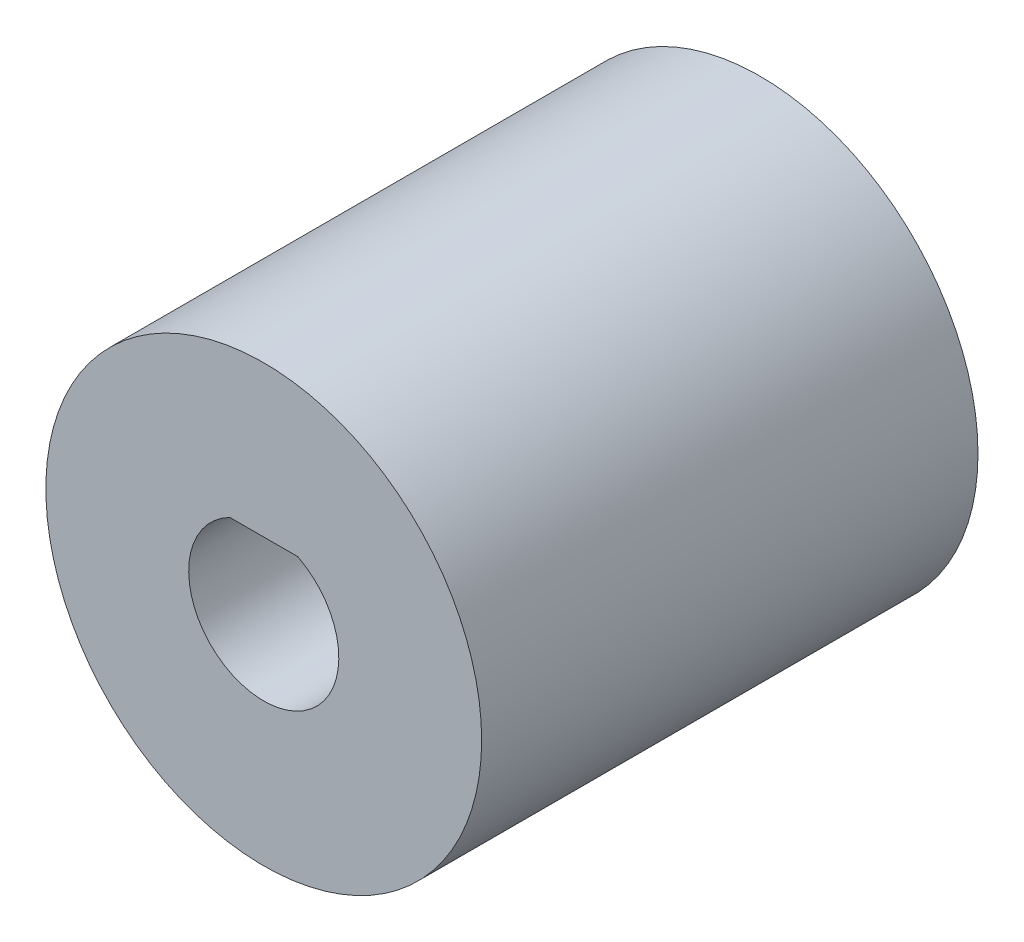
SolidWorks part; units mm, degrees
material "ABS"
ref_plane "Front Plane" through (0, 0, 0) normal (0, 0, 1) x (1, 0, 0)
ref_plane "Top Plane" through (0, 0, 0) normal (0, 1, 0) x (1, 0, 0)
ref_plane "Right Plane" through (0, 0, 0) normal (1, 0, 0) x (0, 0, -1)
sketch "Sketch2" plane through (0, 0, 0) normal (0, 0, 1) x (1, 0, 0)
  circle A0 centre (0, 0) radius 9
  circle A1 centre (0, 0) radius 6
  dimension "D1" = 18
  dimension "D2" = 12
extrude "Large Shaft Cut" add sketch "Sketch2" along normal blind 0.5
ref_plane "Plane1" through (0, 0, 0.5) normal (0, 0, 1) x (1, 0, 0)
sketch "Sketch3" plane through (0, 0, 0.5) normal (0, 0, 1) x (1, 0, 0)
  line L0 (-1.4, 2.7659) -> (1.4, 2.7659)
  circle A0 centre (0, 0) radius 9
  arc A1 (-1.4, 2.7659) -> (1.4, 2.7659) centre (0, 0) ccw
  dimension "D1" = 2.8
  dimension "D2" = 6.2
extrude "Keyed Shaft Cut" add sketch "Sketch3" along normal blind 20
